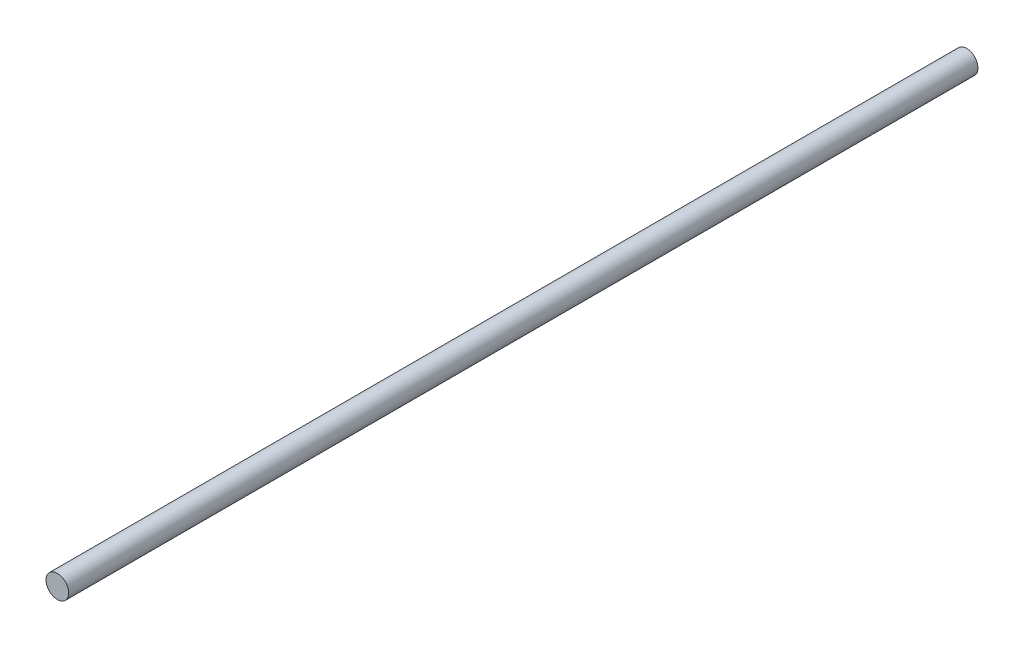
SolidWorks part; units mm, degrees
ref_plane "前视基准面" through (0, 0, 0) normal (0, 0, 1) x (1, 0, 0)
ref_plane "上视基准面" through (0, 0, 0) normal (0, 1, 0) x (1, 0, 0)
ref_plane "右视基准面" through (0, 0, 0) normal (1, 0, 0) x (0, 0, -1)
sketch "草图1" plane through (0, 0, 0) normal (0, 0, 1) x (1, 0, 0)
  circle A0 centre (0, 0) radius 5
  dimension "D1" = 10
extrude "凸台-拉伸1" add sketch "草图1" along normal blind 400
